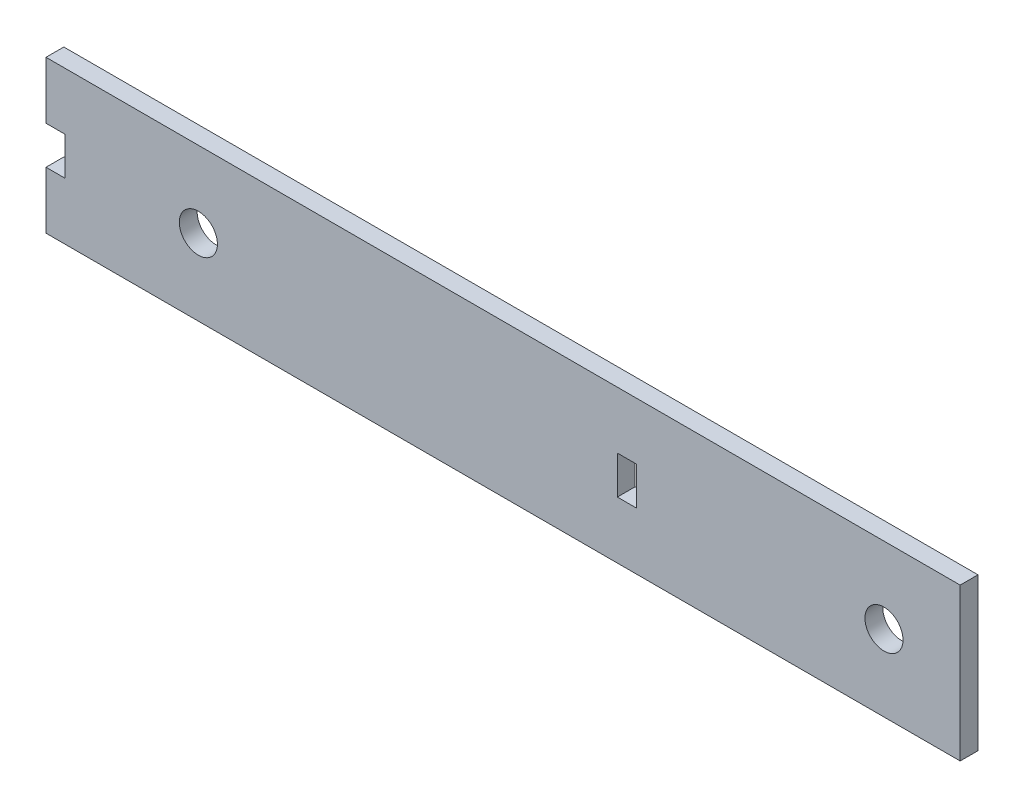
SolidWorks part; units mm, degrees
ref_plane "Front Plane" through (0, 0, 0) normal (1, 0, 0) x (0, 1, 0)
ref_plane "Top Plane" through (0, 0, 0) normal (0, 0, 1) x (0, 1, 0)
ref_plane "Right Plane" through (0, 0, 0) normal (0, 1, 0) x (-1, 0, 0)
sketch "Sketch1" plane through (0, 0, 0) normal (0, 0, 1) x (0, 1, 0)
  line L1 (-12.7, 76.2) -> (12.7, 76.2)
  line L2 (-12.7, 76.2) -> (-12.7, -76.2)
  line L3 (-12.7, -76.2) -> (12.7, -76.2)
  line L4 (12.7, 76.2) -> (12.7, -76.2)
  line L5 (-12.7, 76.2) -> (12.7, -76.2) construction
  line L6 (-12.7, -76.2) -> (12.7, 76.2) construction
  point P0 (0, 0)
  dimension "D1" = 25.4
  dimension "D2" = 152.4
extrude "Boss-Extrude1" add sketch "Sketch1" along normal blind 2.9718
sketch "Sketch7" plane through (0, 0, 2.9718) normal (0, 0, 1) x (1, 0, 0)
  line L0 (-73.9059, 0) -> (82.3338, 0) construction
  line L2 (-76.2, 12.7) -> (-76.2, -12.7) construction
  line L3 (-79.375, -3.175) -> (-73.025, -3.175)
  line L4 (-79.375, -3.175) -> (-79.375, 3.175)
  line L5 (-79.375, 3.175) -> (-73.025, 3.175)
  line L6 (-73.025, -3.175) -> (-73.025, 3.175)
  line L7 (-79.375, -3.175) -> (-73.025, 3.175) construction
  line L8 (-79.375, 3.175) -> (-73.025, -3.175) construction
  line L10 (19.05, -3.1665) -> (22.225, -3.1665)
  line L11 (19.05, -3.1665) -> (19.05, 3.1835)
  line L12 (19.05, 3.1835) -> (22.225, 3.1835)
  line L13 (22.225, -3.1665) -> (22.225, 3.1835)
  line L14 (19.05, -3.1665) -> (22.225, 3.1835) construction
  line L15 (19.05, 3.1835) -> (22.225, -3.1665) construction
  circle A0 centre (-50.8, 0) radius 3.175
  circle A1 centre (63.5, 0) radius 3.175
  point P2 (-76.2, 0)
  point P10 (50.5007, 0.0085)
  point P18 (-69.4655, -3.175)
  point P19 (-57.9578, 3.1767)
  dimension "D5" = 6.35
  dimension "D6" = 6.35
  dimension "D1" = 6.35
  dimension "D2" = 6.35
  dimension "D3" = 3.175
  dimension "D4" = 6.35
  dimension "D7" = 50.8
  dimension "D8" = 63.5
  dimension "D9" = 19.05
extrude "Cut-Extrude5" cut sketch "Sketch7" against normal through all
